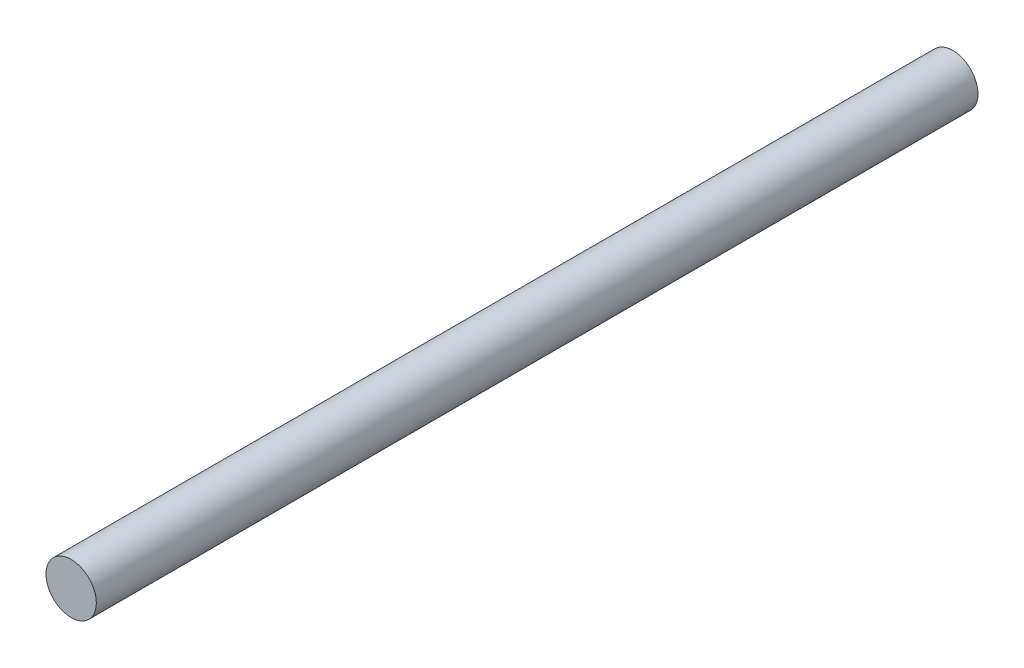
SolidWorks part; units mm, degrees
ref_plane "Front Plane" through (0, 0, 0) normal (0, 0, 1) x (1, 0, 0)
ref_plane "Top Plane" through (0, 0, 0) normal (0, 1, 0) x (1, 0, 0)
ref_plane "Right Plane" through (0, 0, 0) normal (1, 0, 0) x (0, 0, -1)
other "Configuration Table"
sketch "Sketch1" plane through (0, 0, 0) normal (0, 0, 1) x (1, 0, 0)
  circle A0 centre (500, 420) radius 4
extrude "PACK_vakum_hortumu_D8" add sketch "Sketch1" against normal blind 140 from offset 420 separate body
